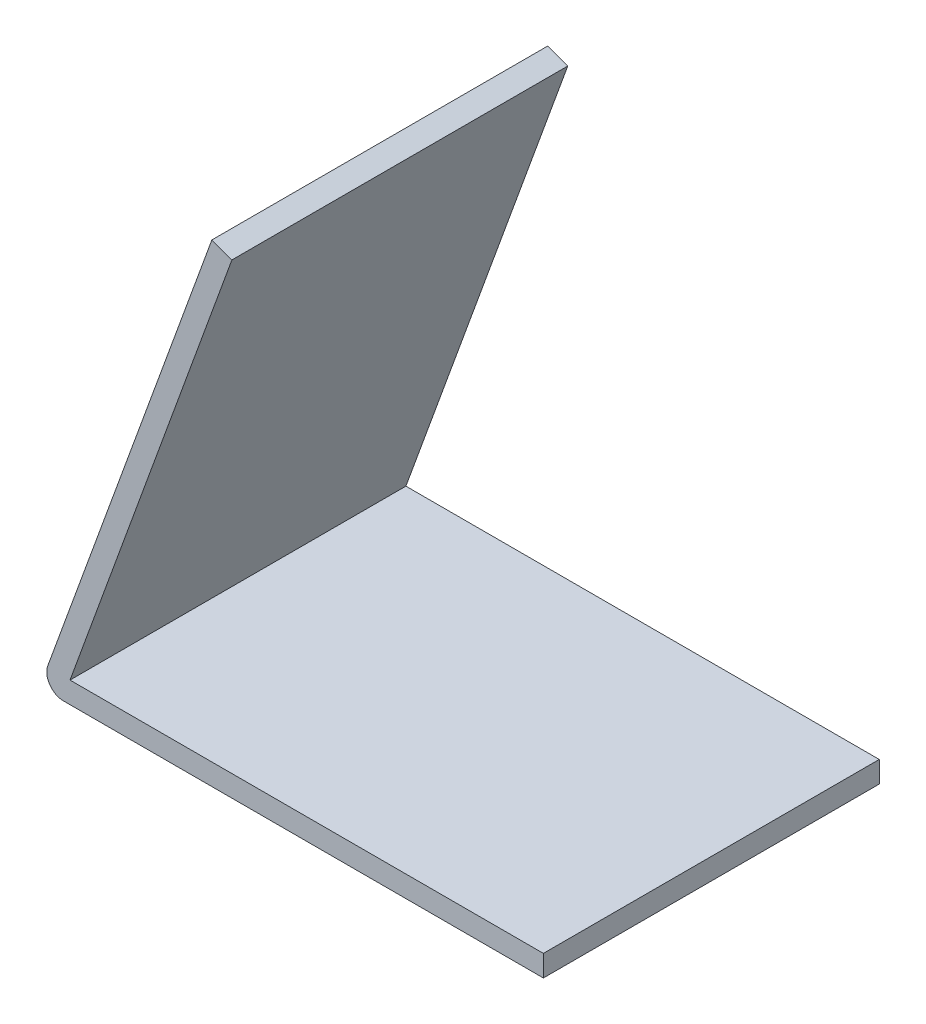
SolidWorks part; units mm, degrees
ref_plane "Front Plane" through (0, 0, 0) normal (0, 0, 1) x (1, 0, 0)
ref_plane "Top Plane" through (0, 0, 0) normal (0, 1, 0) x (1, 0, 0)
ref_plane "Right Plane" through (0, 0, 0) normal (1, 0, 0) x (0, 0, -1)
sketch "Sketch1" plane through (0, 0, 0) normal (0, 0, 1) x (1, 0, 0)
  line L0 (0, 0) -> (140.9313, 0)
  line L1 (0, 0) -> (48.2013, 132.4321)
  line L2 (48.2013, 132.4321) -> (42.2343, 134.6039)
  line L3 (42.2343, 134.6039) -> (-9.0687, -6.35)
  line L4 (-9.0687, -6.35) -> (140.9313, -6.35)
  line L5 (140.9313, -6.35) -> (140.9313, 0)
  dimension "D1" = 6.35
  dimension "D2" = 70
  dimension "D3" = 6.35
  dimension "D4" = 150
  dimension "D5" = 150
extrude "Boss-Extrude1" add sketch "Sketch1" along normal mid plane 100
fillet "Fillet1" radius 5 1 edges at (-9.0687, -6.35, 0)
